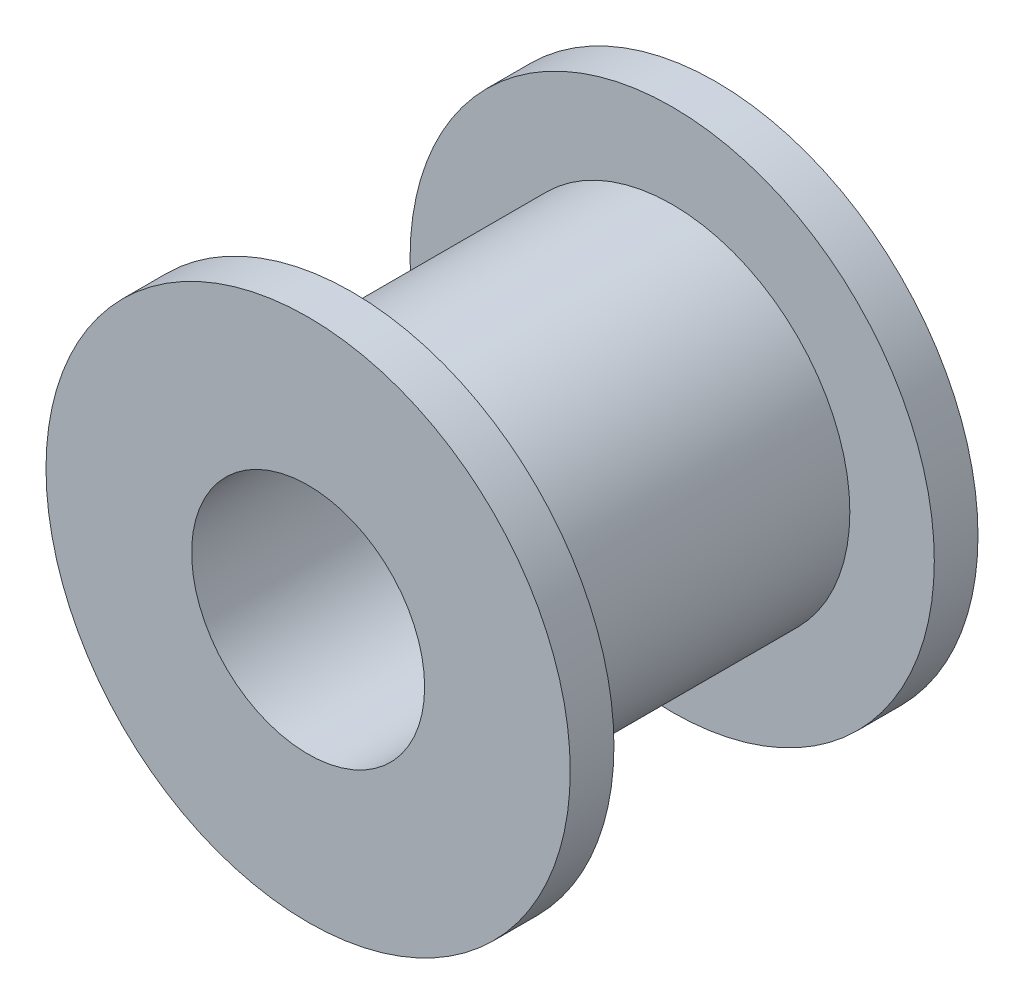
SolidWorks part; units mm, degrees
material "AISI 304"
ref_plane "Front Plane" through (0, 0, 0) normal (0, 0, 1) x (1, 0, 0)
ref_plane "Top Plane" through (0, 0, 0) normal (0, 1, 0) x (1, 0, 0)
ref_plane "Right Plane" through (0, 0, 0) normal (1, 0, 0) x (0, 0, -1)
sketch "Sketch2" plane through (0, 0, 0) normal (0, 0, 1) x (1, 0, 0)
  circle A0 centre (0, 0) radius 9
  dimension "D1" = 18
extrude "Boss-Extrude1" add sketch "Sketch2" along normal blind 1.5
sketch "Sketch3" plane through (0, 0, 1.5) normal (0, 0, 1) x (1, 0, 0)
  circle A0 centre (0, 0) radius 6.1
  dimension "D1" = 12.2
extrude "Boss-Extrude2" add sketch "Sketch3" along normal blind 11
sketch "Sketch4" plane through (0, 0, 12.5) normal (0, 0, 1) x (1, 0, 0)
  circle A0 centre (0, 0) radius 9
  dimension "D1" = 18
extrude "Boss-Extrude3" add sketch "Sketch4" along normal blind 1.5
sketch "Sketch5" plane through (0, 0, 14) normal (0, 0, 1) x (1, 0, 0)
  circle A0 centre (0, 0) radius 4
  dimension "D1" = 8
extrude "Cut-Extrude1" cut sketch "Sketch5" against normal blind 20
